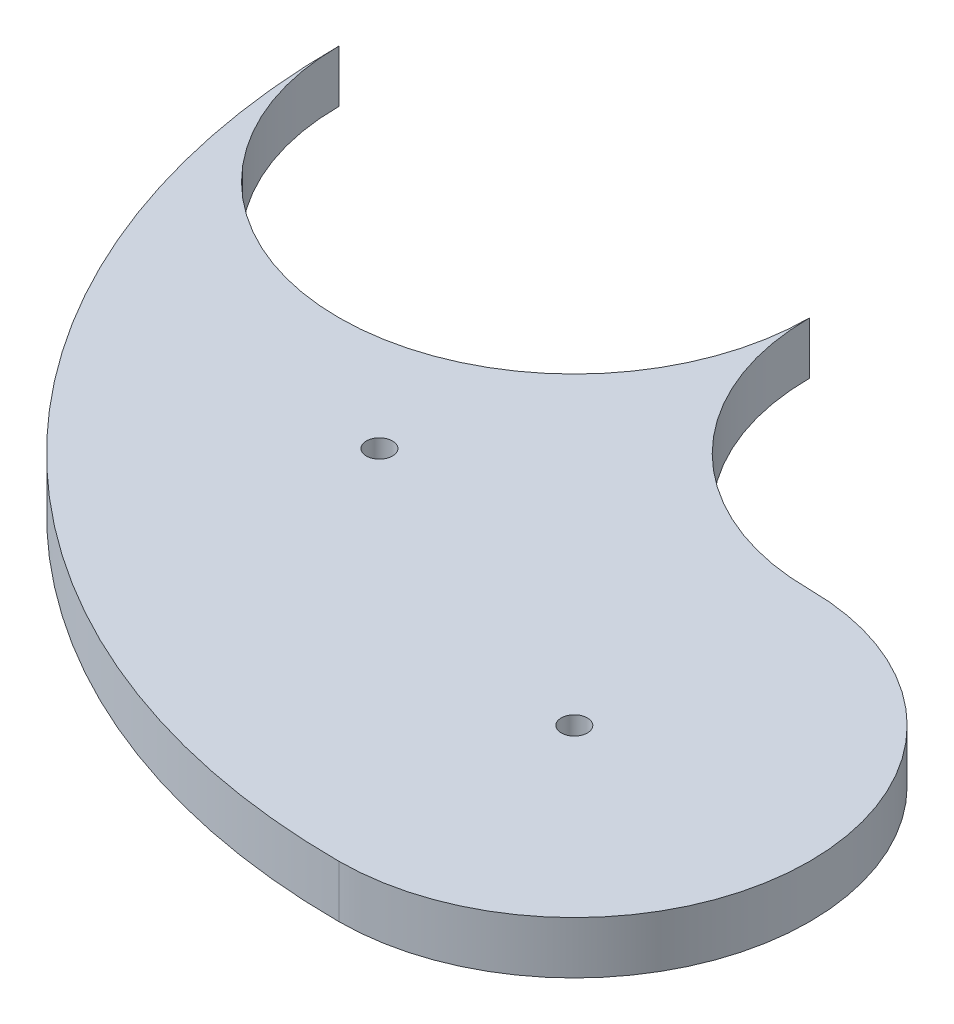
SolidWorks part; units mm, degrees
ref_plane "前基準面" through (0, 0, 0) normal (0, 0, 1) x (1, 0, 0)
ref_plane "上基準面" through (0, 0, 0) normal (0, 1, 0) x (1, 0, 0)
ref_plane "右基準面" through (0, 0, 0) normal (1, 0, 0) x (0, 0, -1)
sketch "草圖1" plane through (0, 0, 0) normal (0, 1, 0) x (1, 0, 0)
  line L0 (0, 0) -> (0, 45) construction
  line L1 (0, 45) -> (-45, 45) construction
  circle A0 centre (0, 0) radius 1.2295 construction
  circle A1 centre (-32.245, 13.6111) radius 1.2295 construction
  arc A2 (-67.5, 45) -> (0, -22.5) centre (0, 45) ccw
  arc A3 (0, -22.5) -> (0, 22.5) centre (0, 0) ccw
  arc A4 (-22.5, 45) -> (0, 22.5) centre (0, 45) ccw
  arc A5 (-67.5, 45) -> (-22.5, 45) centre (-45, 45) ccw
  arc A6 (0, 0) -> (-45, 45) centre (0, 45) cw construction
  point P1 (-2.5533, 16.0439)
  point P12 (0, 0)
  point P13 (-2.5533, 16.0439)
  point P14 (0, 0)
  dimension "D1" = 35
  dimension "D2" = 67.5
  dimension "D3" = 22.5
  dimension "D4" = 45
extrude "填料-伸長1" add sketch "草圖1" against normal blind 5 contours A5 A4 A3 A2
hole_wizard "M3 螺紋孔1" positions "草圖2" profile "草圖3" tap size "M3" standard "ISO" end condition through all
sketch "草圖2" plane through (0, 0, 0) normal (0, 1, 0) x (1, 0, 0)
  point P0 (-32.245, 13.6111)
  point P3 (0, 0)
sketch "草圖3" plane through (-32.245, 0, -13.6111) normal (1, 0, 0) x (0, 0, 1)
  line L0 (0, 0) -> (0, 5)
  line L1 (0, 5) -> (1.25, 5)
  line L2 (1.25, 5) -> (1.25, 0)
  line L5 (1.25, 0) -> (0, 0)
  line L11 (0, -6.35) -> (0, 107.95) construction
  dimension "貫穿螺孔鑽直徑" = 2.5
  dimension "貫穿螺孔鑽深度" = 5
cosmetic thread "鑽孔螺紋1" parameters "D2"=3
cosmetic thread "鑽孔螺紋2" parameters "D2"=3
